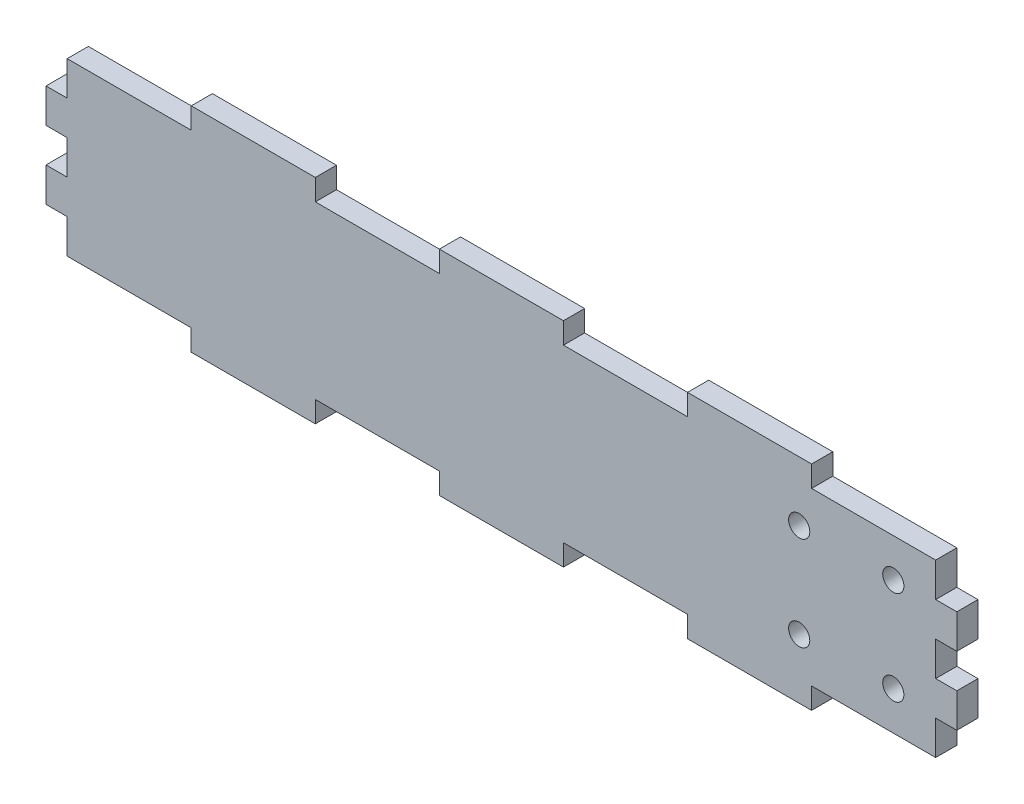
SolidWorks part; units mm, degrees
ref_plane "Front Plane" through (0, 0, 0) normal (0, 0, 1) x (1, 0, 0)
ref_plane "Top Plane" through (0, 0, 0) normal (0, 1, 0) x (1, 0, 0)
ref_plane "Right Plane" through (0, 0, 0) normal (1, 0, 0) x (0, 0, -1)
sketch "Sketch2" plane through (0, 0, 0) normal (0, 0, 1) x (1, 0, 0)
  line L0 (0, 40.4) -> (0, 0) construction
  line L4 (205.1, 40.4) -> (205.1, 24.24)
  line L7 (205.1, 24.24) -> (215.1, 24.24)
  line L8 (205.1, 8.08) -> (215.1, 8.08)
  line L11 (-205.1, 0) -> (205.1, 0) construction
  line L13 (205.1, 8.08) -> (205.1, -8.08)
  line L15 (215.1, 8.08) -> (215.1, 24.24)
  line L16 (205.1, 40.4) -> (146.5, 40.4)
  line L38 (29.3, 40.4) -> (87.9, 40.4)
  line L39 (0, -40.4) -> (0, 0) construction
  line L40 (146.5, 40.4) -> (146.5, 50.4)
  line L41 (87.9, 40.4) -> (87.9, 50.4)
  line L42 (29.3, 40.4) -> (29.3, 50.4)
  line L56 (205.1, 40.4) -> (205.1, 24.24)
  line L57 (146.5, 50.4) -> (87.9, 50.4)
  line L59 (87.9, 40.4) -> (29.3, 40.4)
  line L60 (146.5, 40.4) -> (205.1, 40.4)
  line L61 (29.3, 50.4) -> (-29.3, 50.4)
  line L62 (29.3, -50.4) -> (-29.3, -50.4)
  line L63 (146.5, -40.4) -> (205.1, -40.4)
  line L64 (87.9, -40.4) -> (29.3, -40.4)
  line L66 (146.5, -50.4) -> (87.9, -50.4)
  line L67 (29.3, -40.4) -> (29.3, -50.4)
  line L68 (87.9, -40.4) -> (87.9, -50.4)
  line L69 (146.5, -40.4) -> (146.5, -50.4)
  line L70 (29.3, -40.4) -> (87.9, -40.4)
  line L71 (205.1, -40.4) -> (146.5, -40.4)
  line L72 (215.1, -8.08) -> (215.1, -24.24)
  line L73 (205.1, -8.08) -> (215.1, -8.08)
  line L74 (205.1, -24.24) -> (215.1, -24.24)
  line L75 (205.1, -40.4) -> (205.1, -24.24)
  line L76 (-205.1, -40.4) -> (-205.1, -24.24)
  line L77 (-205.1, -24.24) -> (-215.1, -24.24)
  line L78 (-205.1, -8.08) -> (-215.1, -8.08)
  line L79 (-215.1, -8.08) -> (-215.1, -24.24)
  line L80 (-205.1, -40.4) -> (-146.5, -40.4)
  line L81 (-29.3, -40.4) -> (-87.9, -40.4)
  line L82 (-146.5, -40.4) -> (-146.5, -50.4)
  line L83 (-87.9, -40.4) -> (-87.9, -50.4)
  line L84 (-29.3, -40.4) -> (-29.3, -50.4)
  line L85 (-146.5, -50.4) -> (-87.9, -50.4)
  line L86 (-87.9, -40.4) -> (-29.3, -40.4)
  line L87 (-146.5, -40.4) -> (-205.1, -40.4)
  line L88 (-146.5, 40.4) -> (-205.1, 40.4)
  line L89 (-87.9, 40.4) -> (-29.3, 40.4)
  line L90 (-146.5, 50.4) -> (-87.9, 50.4)
  line L91 (-205.1, 40.4) -> (-205.1, 24.24)
  line L92 (-29.3, 40.4) -> (-29.3, 50.4)
  line L96 (-87.9, 40.4) -> (-87.9, 50.4)
  line L97 (-146.5, 40.4) -> (-146.5, 50.4)
  line L98 (-29.3, 40.4) -> (-87.9, 40.4)
  line L99 (-205.1, 40.4) -> (-146.5, 40.4)
  line L100 (-215.1, 8.08) -> (-215.1, 24.24)
  line L101 (-205.1, 8.08) -> (-205.1, -8.08)
  line L102 (-205.1, 8.08) -> (-215.1, 8.08)
  line L103 (-205.1, 24.24) -> (-215.1, 24.24)
  line L104 (-205.1, 40.4) -> (-205.1, 24.24)
  line L105 (205.1, 8.08) -> (205.1, -8.08)
  line L106 (205.1, -24.24) -> (205.1, -40.4)
  line L107 (-205.1, -24.24) -> (-205.1, -40.4)
  line L108 (-205.1, 8.08) -> (-205.1, -8.08)
  point P0 (0, 0)
  point P18 (0, 20.2)
  point P33 (0, -20.2)
  dimension "D2" = 205.1
extrude "Boss-Extrude1" add sketch "Sketch2" along normal blind 10 contours L91 L103 L100 L102 L101 L78 L79 L77 L76 L80 L82 L85 L83 L81 L84 L62 L67 L64 L68 L66 L69 L63 L75 L74 L72 L73 L13 L8 L15 L7 L4 L16 L40 L57 L41 L38 L42 L61 L92 L89 L96 L90 L97 L88
sketch "Sketch3" plane through (0, 0, 10) normal (0, 0, 1) x (1, 0, 0)
  line L0 (140.65, 22.225) -> (185.1, 22.225) construction
  line L1 (140.65, 22.225) -> (140.65, -22.225) construction
  line L2 (140.65, -22.225) -> (185.1, -22.225) construction
  line L3 (185.1, 22.225) -> (185.1, -22.225) construction
  line L4 (140.65, 22.225) -> (185.1, -22.225) construction
  line L5 (140.65, -22.225) -> (185.1, 22.225) construction
  line L6 (205.1, 0) -> (191.6766, 0) construction
  line L7 (205.1, 8.08) -> (205.1, -8.08) construction
  circle A0 centre (185.1, 22.225) radius 5
  circle A4 centre (140.65, 22.225) radius 5
  circle A5 centre (140.65, -22.225) radius 5
  circle A6 centre (185.1, -22.225) radius 5
  point P0 (162.875, 0)
  dimension "D2" = 10
  dimension "D1" = 44.45
  dimension "D3" = 2
  dimension "D4" = 20
extrude "Cut-Extrude1" cut sketch "Sketch3" against normal through all
